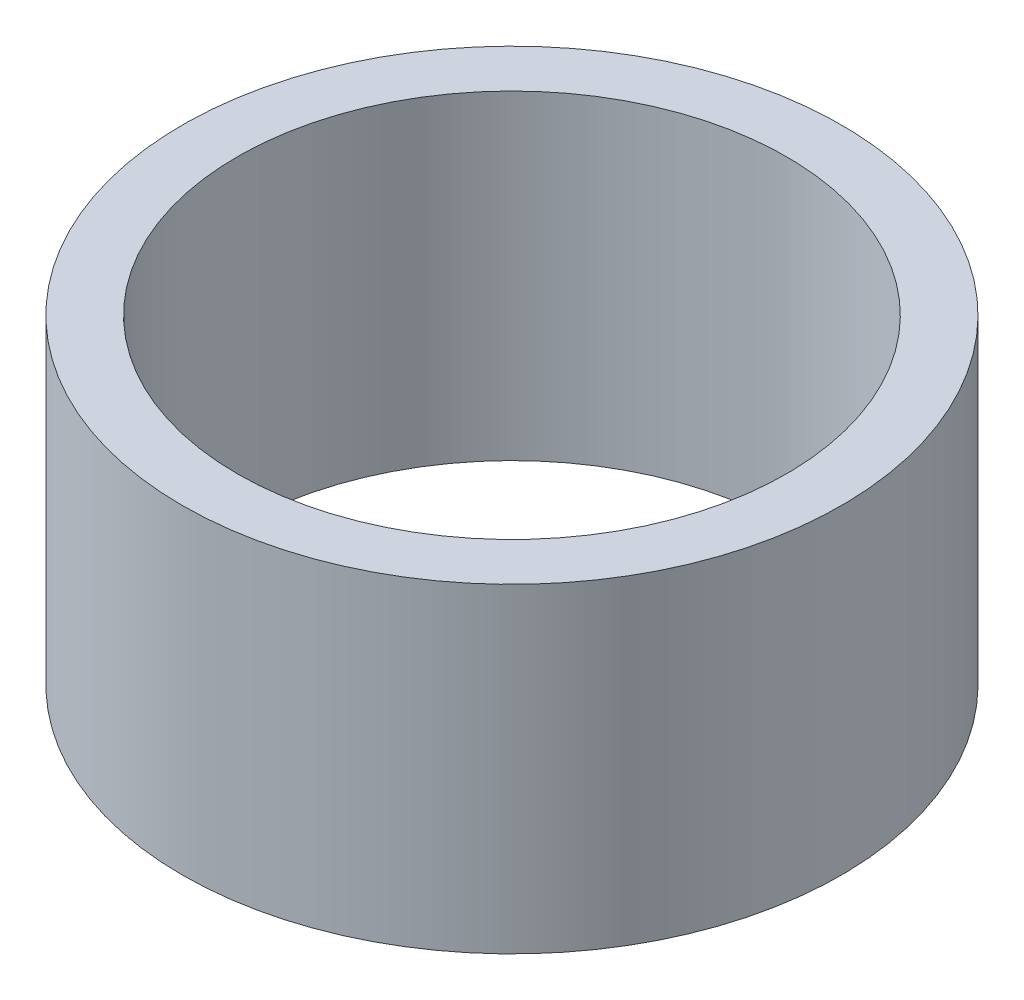
SolidWorks part; units mm, degrees
material "AISI 1020 Steel, Cold Rolled"
ref_plane "Front Plane" through (0, 0, 0) normal (0, 0, 1) x (1, 0, 0)
ref_plane "Top Plane" through (0, 0, 0) normal (0, 1, 0) x (1, 0, 0)
ref_plane "Right Plane" through (0, 0, 0) normal (1, 0, 0) x (0, 0, -1)
sketch "Sketch1" plane through (0, 0, 0) normal (0, 1, 0) x (1, 0, 0)
  circle A0 centre (0, 0) radius 7.9375
  circle A1 centre (0, 0) radius 9.525
  dimension "D1" = 15.875
  dimension "D2" = 19.05
extrude "Boss-Extrude1" add sketch "Sketch1" along normal blind 9.25
